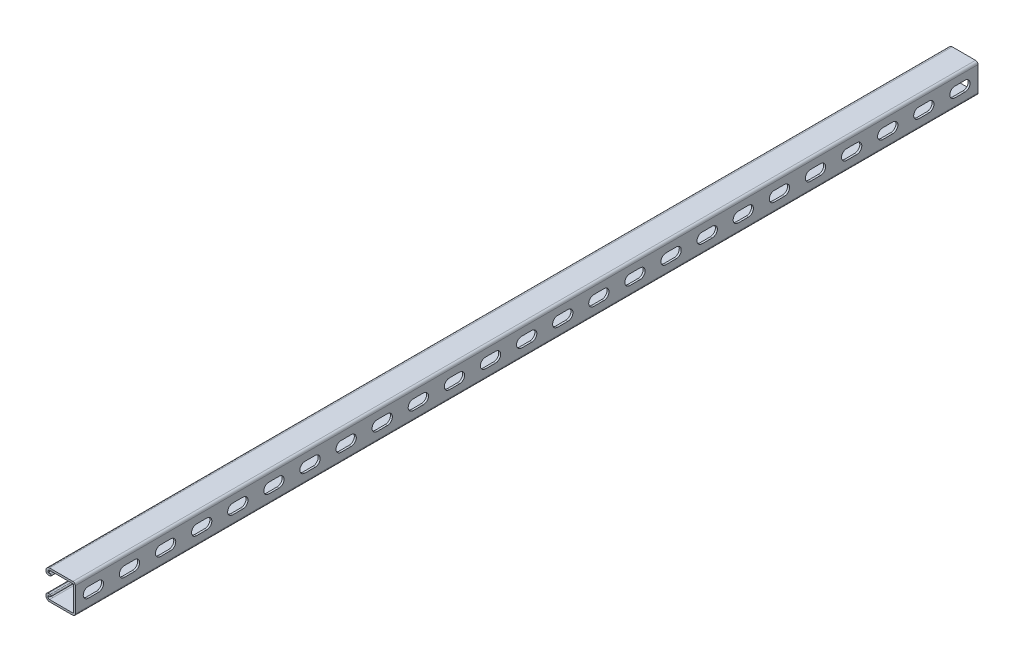
SolidWorks part; units mm, degrees
ref_plane "Front Plane" through (0, 0, 0) normal (0, 0, 1) x (1, 0, 0)
ref_plane "Top Plane" through (0, 0, 0) normal (0, 1, 0) x (1, 0, 0)
ref_plane "Right Plane" through (0, 0, 0) normal (1, 0, 0) x (0, 0, -1)
sketch "Sketch1" plane through (0, 0, 0) normal (0, 0, 1) x (1, 0, 0)
  line L0 (0, 0) -> (-41.275, 0) construction
  line L3 (-41.275, 20.6375) -> (0, 20.6375) construction
  line L4 (-41.275, 20.6375) -> (-41.275, -20.6375) construction
  line L5 (-41.275, -20.6375) -> (0, -20.6375) construction
  line L6 (0, 20.6375) -> (0, -20.6375) construction
  line L7 (-36.2267, 20.6375) -> (-3.4607, 20.6375)
  line L8 (0, 17.1767) -> (0, -17.1767)
  line L9 (-2.794, -17.1767) -> (-2.794, 17.1767)
  line L10 (-3.4608, 17.8435) -> (-36.2267, 17.8435)
  line L11 (-41.275, 15.5892) -> (-41.275, 14.5732)
  line L12 (-37.8142, 11.1125) -> (-35.5346, 11.1125)
  line L14 (-35.5346, 13.9065) -> (-37.8142, 13.9065)
  line L15 (-38.481, 14.5732) -> (-38.481, 15.5892)
  line L16 (-38.481, -14.5733) -> (-38.481, -15.5893)
  line L17 (-35.5346, -13.9065) -> (-37.8142, -13.9065)
  line L18 (-37.8142, -11.1125) -> (-35.5346, -11.1125)
  line L19 (-41.275, -15.5893) -> (-41.275, -14.5733)
  line L20 (-3.4607, -17.8435) -> (-36.2267, -17.8435)
  line L21 (-36.2267, -20.6375) -> (-3.4607, -20.6375)
  line L22 (-2.794, -20.6375) -> (-2.794, 20.6375) construction
  arc A1 (0, 17.1767) -> (-3.4607, 20.6375) centre (-3.4607, 17.1767) ccw
  arc A2 (-2.794, 17.1767) -> (-3.4608, 17.8435) centre (-3.4607, 17.1767) ccw
  arc A4 (-36.2267, 20.6375) -> (-41.275, 15.5892) centre (-36.2267, 15.5892) ccw
  arc A5 (-41.275, 14.5732) -> (-37.8142, 11.1125) centre (-37.8142, 14.5732) ccw
  arc A6 (-35.5346, 11.1125) -> (-35.5346, 13.9065) centre (-35.5346, 12.5095) ccw
  arc A7 (-37.8142, 13.9065) -> (-38.481, 14.5732) centre (-37.8142, 14.5732) cw
  arc A8 (-38.481, 15.5892) -> (-36.2267, 17.8435) centre (-36.2267, 15.5892) cw
  arc A9 (-38.481, -15.5893) -> (-36.2267, -17.8435) centre (-36.2267, -15.5893) ccw
  arc A10 (-37.8142, -13.9065) -> (-38.481, -14.5733) centre (-37.8142, -14.5733) ccw
  arc A11 (-35.5346, -11.1125) -> (-35.5346, -13.9065) centre (-35.5346, -12.5095) cw
  arc A12 (-41.275, -14.5733) -> (-37.8142, -11.1125) centre (-37.8142, -14.5733) cw
  arc A13 (-36.2267, -20.6375) -> (-41.275, -15.5893) centre (-36.2267, -15.5893) cw
  arc A14 (-2.794, -17.1767) -> (-3.4607, -17.8435) centre (-3.4607, -17.1767) cw
  arc A15 (0, -17.1767) -> (-3.4607, -20.6375) centre (-3.4607, -17.1767) cw
  point P24 (0, 20.6375)
  point P65 (-2.794, 0)
  dimension "D1" = 3.4608
  dimension "D2" = 5.0482
  dimension "D3" = 3.4608
  dimension "Ht." = 41.275
  dimension "Wd." = 41.275
  dimension "Thk." = 2.794
  dimension "D4" = 9.525
  dimension "D5" = 7.1374
extrude "Boss-Extrude1" add sketch "Sketch1" against normal blind 1270
sketch "Sketch3" plane through (0, 0, 0) normal (1, 0, 0) x (0, 0, -1)
  line L0 (0, 0) -> (1270, 0) construction
  point P2 (101.6, 0)
  point P3 (1168.4, 0)
  dimension "D1" = 101.6
  dimension "D2" = 101.6
  dimension "D3" = 1270
sketch "Sketch2" plane through (0, 0, 0) normal (1, 0, 0) x (0, 0, -1)
  line L0 (18.2562, 0) -> (32.5437, 0) construction
  line L1 (18.2562, 7.1437) -> (32.5437, 7.1437)
  line L2 (18.2562, -7.1437) -> (32.5437, -7.1437)
  line L3 (18.2562, 0) -> (0, 0) construction
  line L4 (25.4, 0) -> (76.2, 0) construction
  line L5 (0, -17.1767) -> (0, 17.1767) construction
  arc A0 (18.2562, 7.1437) -> (18.2562, -7.1437) centre (18.2562, 0) ccw
  arc A1 (32.5437, -7.1437) -> (32.5437, 7.1437) centre (32.5437, 0) ccw
  point P3 (25.4, 0)
  dimension "Hole to End" = 11.1125
  dimension "D2" = 25.4
extrude "Cut-Extrude1" cut sketch "Sketch2" against normal up to vertex (2.794 mm away) up to point (-2.794, 0, 0)
pattern_linear "LPattern1" count 25 spacing 50.8 along (0, 0, -1) of "Cut-Extrude1"
equation "\"D1@LPattern1\" = \"Slot Ctr.@Sketch2\""
equation "\"Hole Count@LPattern1\" = \"Lg.@Boss-Extrude1\" / \"D1@LPattern1\""
equation "\"D3@Sketch3\" = \"Lg.@Boss-Extrude1\""
